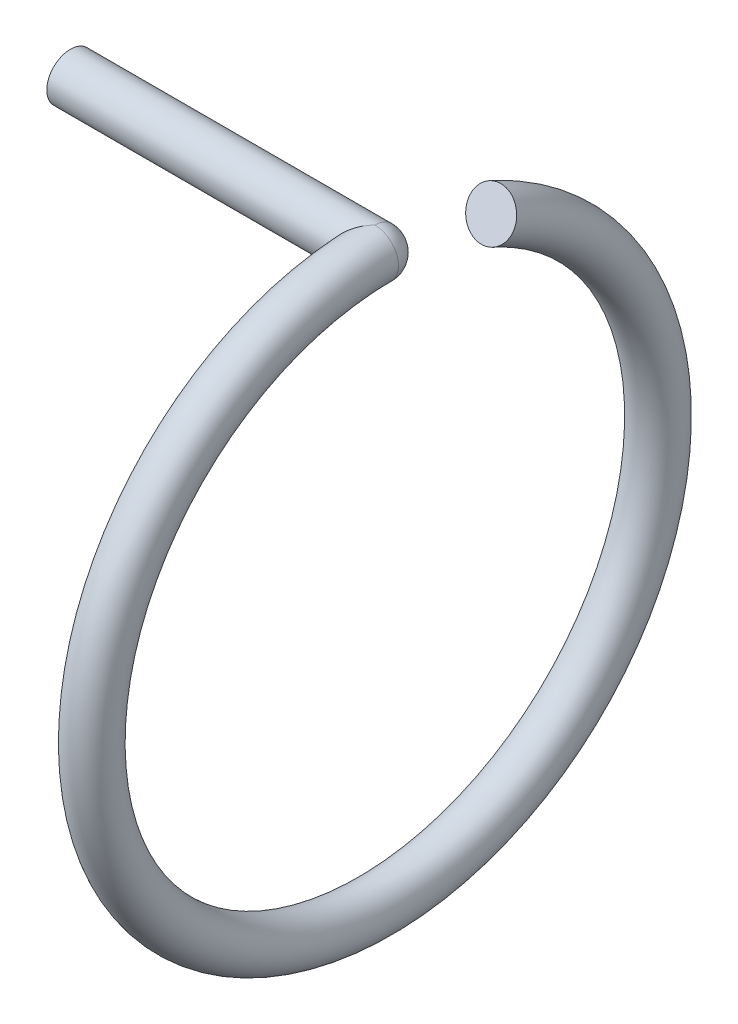
SolidWorks part; units mm, degrees
ref_plane "Front Plane" through (0, 0, 0) normal (0, 0, 1) x (1, 0, 0)
ref_plane "Top Plane" through (0, 0, 0) normal (0, 1, 0) x (1, 0, 0)
ref_plane "Right Plane" through (0, 0, 0) normal (1, 0, 0) x (0, 0, -1)
sketch "Sketch5" plane through (0, 0, 0) normal (1, 0, 0) x (0, 0, -1)
  arc A0 (0, 38.1) -> (15.6466, 34.7389) centre (0, 0) ccw
  dimension "D1" = 38.1
sketch "Sketch6" plane through (0, 0, 0) normal (0, 0, 1) x (1, 0, 0)
  line L0 (0, -38.1) -> (0, 38.1) construction
  circle A0 centre (0, 38.1) radius 3.175
sweep "Sweep1" add profiles "Sketch6" path "Sketch5"
sketch "Sketch7" plane through (0, 0, 0) normal (0, 0, 1) x (1, 0, 0)
  line L0 (0, 38.1) -> (-40.9764, 38.1)
sketch "Sketch8" plane through (0, 0, 0) normal (1, 0, 0) x (0, 0, -1)
  line L0 (0, 34.925) -> (0, 41.275) construction
  circle A0 centre (0, 38.1) radius 3.175
sweep "Sweep2" add profiles "Sketch8" path "Sketch7"
sketch "Sketch9" plane through (0, 0, 0) normal (1, 0, 0) x (0, 0, -1)
  line L1 (0, 0) -> (0, 29.6673) construction
  line L2 (0, 34.925) -> (0, 41.275) construction
  line L3 (0, 41.275) -> (0, 34.925)
  arc A1 (0, 34.925) -> (0, 41.275) centre (0, 38.1) ccw
  arc A2 (0, 34.925) -> (0, 41.275) centre (0, 38.1) ccw construction
revolve "Revolve7" add sketch "Sketch9" angle 360 about L1
